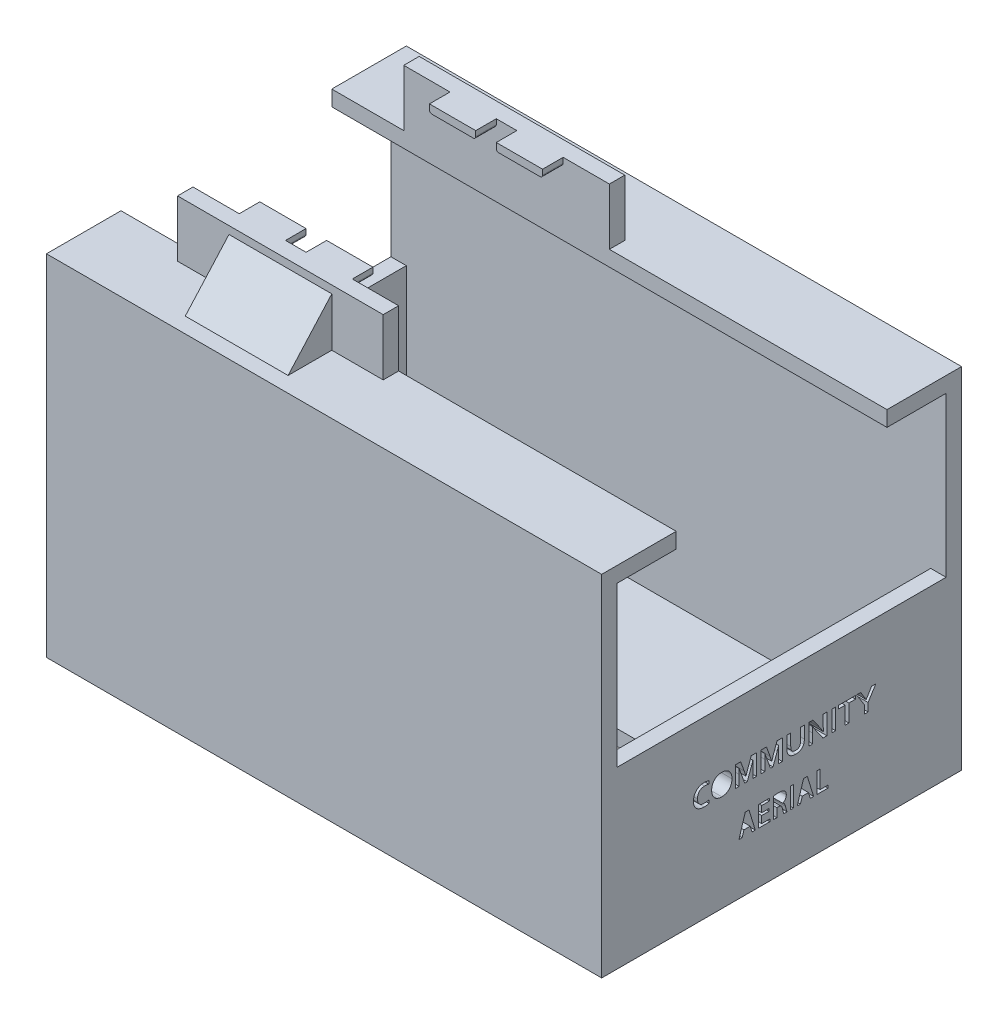
SolidWorks part; units mm, degrees
ref_plane "Alzado" through (0, 0, 0) normal (0, 0, 1) x (1, 0, 0)
ref_plane "Planta" through (0, 0, 0) normal (0, 1, 0) x (1, 0, 0)
ref_plane "Vista lateral" through (0, 0, 0) normal (1, 0, 0) x (0, 0, -1)
sketch "Croquis1" plane through (0, 0, 0) normal (0, 1, 0) x (1, 0, 0)
  line L0 (-2, 20.5) -> (-2, -20.5)
  line L1 (-20, -23.5) -> (20, -23.5)
  line L2 (-20, -23.5) -> (-20, 23.5)
  line L3 (-20, 23.5) -> (20, 23.5)
  line L4 (20, -23.5) -> (20, 23.5)
  line L5 (17, -20.5) -> (2, -20.5)
  line L6 (17, -20.5) -> (17, 20.5)
  line L7 (17, 20.5) -> (2, 20.5)
  line L8 (-17, -20.5) -> (-17, 20.5)
  line L9 (2, 20.5) -> (2, -20.5)
  line L10 (-2, -20.5) -> (-17, -20.5)
  line L11 (-2, 20.5) -> (-17, 20.5)
  line L12 (-55, 0) -> (55, 0) construction
  point P0 (0, 0)
  point P6 (0, 0)
  point P15 (-17, 0)
  dimension "D1" = 47
  dimension "D2" = 40
  dimension "D3" = 3
  dimension "D4" = 3
  dimension "D5" = 3
  dimension "D6" = 15
  dimension "D7" = 15
  dimension "D8" = 3
extrude "Saliente-Extruir1" add sketch "Croquis1" along normal blind 3
sketch "Croquis3" plane through (0, 3, 0) normal (0, 1, 0) x (1, 0, 0)
  line L0 (20, -23.5) -> (20, 23.5) construction
  line L1 (-20, 23.5) -> (20, 23.5)
  line L2 (-20, 23.5) -> (-20, 20.5)
  line L3 (-20, 20.5) -> (20, 20.5)
  line L4 (20, 23.5) -> (20, 20.5)
  line L6 (-20, -23.5) -> (20, -23.5)
  line L7 (-20, -23.5) -> (-20, -20.5)
  line L8 (-20, -20.5) -> (20, -20.5)
  line L9 (20, -23.5) -> (20, -20.5)
  dimension "D1" = 3
  dimension "D2" = 3
extrude "Saliente-Extruir2" add sketch "Croquis3" along normal blind 5
sketch "Croquis5" plane through (0, 0, -20.5) normal (0, 0, 1) x (1, 0, 0)
  line L0 (0, -55) -> (0, 55) construction
  line L1 (-10.5, 6.5) -> (-2.5, 6.5)
  line L2 (-11, 7) -> (-11, 8)
  line L3 (-11, 8) -> (-2, 8)
  line L4 (-2, 7) -> (-2, 8)
  line L5 (-11, 6.5) -> (-2, 8) construction
  line L6 (-11, 8) -> (-2, 6.5) construction
  line L7 (11, 8) -> (2, 6.5) construction
  line L8 (11, 6.5) -> (2, 8) construction
  line L9 (2, 7) -> (2, 8)
  line L10 (11, 8) -> (2, 8)
  line L11 (11, 7) -> (11, 8)
  line L12 (10.5, 6.5) -> (2.5, 6.5)
  line L13 (-20, 8) -> (20, 8) construction
  arc A0 (-2.5, 6.5) -> (-2, 7) centre (-2.5, 7) ccw
  arc A1 (-10.5, 6.5) -> (-11, 7) centre (-10.5, 7) cw
  arc A2 (10.5, 6.5) -> (11, 7) centre (10.5, 7) ccw
  arc A3 (2.5, 6.5) -> (2, 7) centre (2.5, 7) cw
  point P0 (-6.5, 7.25)
  point P11 (6.5, 7.25)
  dimension "D5" = 0.5
  dimension "D6" = 0.5
  dimension "D1" = 9
  dimension "D2" = 1.5
  dimension "D3" = 6.5
  dimension "D4" = 0
extrude "Saliente-Extruir3" add sketch "Croquis5" along normal blind 4
mirror "Simetría3" about plane through (0, 0, 0) normal (0, 0, 1) of "Saliente-Extruir3"
sketch "Croquis6" plane through (0, 0, 0) normal (0, -1, 0) x (1, 0, 0)
  line L0 (20, 23.5) -> (20, -23.5) construction
  line L1 (-20, 23.5) -> (20, 23.5)
  line L2 (-20, 23.5) -> (-20, 20.5)
  line L3 (-20, 20.5) -> (20, 20.5)
  line L4 (20, 23.5) -> (20, 20.5)
  line L5 (4.4, 0) -> (-4.4, 0) construction
  line L6 (20, -23.5) -> (20, -20.5)
  line L7 (-20, -20.5) -> (20, -20.5)
  line L8 (-20, -23.5) -> (-20, -20.5)
  line L9 (-20, -23.5) -> (20, -23.5)
  dimension "D1" = 3
extrude "Saliente-Extruir4" add sketch "Croquis6" along normal blind 3
ref_plane "Plano1" through (20, 0, 0) normal (1, 0, 0) x (0, 0, -1)
sketch "Croquis8" plane through (20, 0, 0) normal (1, 0, 0) x (0, 0, -1)
  line L1 (-32, -68) -> (32, -68)
  line L2 (-32, -68) -> (-32, -6)
  line L3 (-32, -6) -> (-20.5, -6)
  line L4 (32, -68) -> (32, -6)
  line L5 (20.5, -6) -> (32, -6)
  line L6 (20.5, -3) -> (35, -3)
  line L9 (-35, -71) -> (35, -71)
  line L10 (-35, -71) -> (-35, -3)
  line L11 (-35, -3) -> (-20.5, -3)
  line L12 (35, -71) -> (35, -3)
  line L16 (20.5, -3) -> (20.5, -6)
  line L17 (-20.5, -3) -> (-20.5, -6)
  point P0 (0, -37)
  point P11 (0, -37)
  dimension "D1" = 64
  dimension "D2" = 62
  dimension "D4" = 3
  dimension "D5" = 3
extrude "Saliente-Extruir5" add sketch "Croquis8" along normal mid plane 108
sketch "Croquis9" plane through (0, 0, 0) normal (0, 0, 1) x (1, 0, 0)
  line L0 (20, -38.5) -> (20, 38.5) construction
  line L1 (-34, -71) -> (-31, -71)
  line L2 (-34, -71) -> (-34, -37)
  line L3 (-34, -37) -> (-31, -37)
  line L4 (-31, -71) -> (-31, -37)
  line L5 (71, -71) -> (71, -37)
  line L6 (74, -37) -> (71, -37)
  line L7 (74, -71) -> (74, -37)
  line L8 (74, -71) -> (71, -71)
  dimension "D1" = 3
extrude "Saliente-Extruir6" add sketch "Croquis9" along normal mid plane 68
sketch "Croquis10" plane through (0, 0, 0) normal (1, 0, 0) x (0, 0, -1)
  line L1 (-20.5, -3) -> (20.5, -3)
  line L2 (-20.5, -3) -> (-20.5, 3)
  line L3 (-20.5, 3) -> (20.5, 3)
  line L4 (20.5, -3) -> (20.5, 3)
  line L5 (-20.5, -3) -> (20.5, 3) construction
  line L6 (-20.5, 3) -> (20.5, -3) construction
  point P0 (0, 0)
extrude "Cortar-Extruir1" cut sketch "Croquis10" against normal mid plane 68
sketch "Croquis11" plane through (0, 0, 0) normal (1, 0, 0) x (0, 0, -1)
  line L0 (-32, -3) -> (-23.5, 6.5)
  line L1 (-20.5, -3) -> (-35, -3) construction
  line L2 (-23.5, 8) -> (-23.5, -3) construction
rib "Nervio1" sketch "Croquis11" sketch "Croquis11" thickness 20 extrusion direction parallel to sketch draft on no parameters "D1"=20
mirror "Simetría4" about plane through (0, 0, 0) normal (0, 0, 1) of "Nervio1"
sketch "Croquis12" plane through (0, -71, 0) normal (0, -1, 0) x (1, 0, 0)
  line L0 (43.45, 0) -> (-43.45, 0) construction
  line L1 (11, -5.5) -> (71, -5.5)
  line L2 (11, -5.5) -> (11, 5.5)
  line L3 (11, 5.5) -> (71, 5.5)
  line L4 (71, -5.5) -> (71, 5.5)
  line L5 (11, -5.5) -> (71, 5.5) construction
  line L6 (11, 5.5) -> (71, -5.5) construction
  line L7 (74, 35) -> (74, -35) construction
  point P0 (41, 0)
  dimension "D1" = 11
  dimension "D2" = 33
  dimension "D3" = 60
extrude "Cortar-Extruir2" cut sketch "Croquis12" against normal blind 68
sketch "Croquis13" plane through (74, 0, 0) normal (1, 0, 0) x (0, 0, -1)
  line L0 (-21.5696, -52.1006) -> (21.5696, -52.1006) construction
  line L1 (0, 43.45) -> (0, -43.45) construction
  line L2 (-12.5252, -61.0353) -> (12.5252, -61.0353) construction
  text T0 "<b>COMMUNITY</b>" font "Corbel" height 4
  text T1 "<b>AERIAL</b>" font "Adobe Heiti Std R" height 4
  point P2 (0, -52.1006)
  point P8 (0, -61.0353)
extrude "Cortar-Extruir4" cut sketch "Croquis13" against normal blind 4
sketch "Croquis14" plane through (74, 0, 0) normal (1, 0, 0) x (0, 0, -1)
  line L0 (-7.4196, -59.3544) -> (-6.8994, -57.1681)
  line L1 (-6.8994, -57.1681) -> (-5.6422, -59.6435)
  line L2 (-5.6422, -59.6435) -> (-7.4196, -59.6435)
  line L3 (-7.4196, -59.6435) -> (-7.4196, -59.3544)
  line L4 (3.7944, -59.3544) -> (4.5491, -57.3556)
  line L5 (4.5491, -57.3556) -> (5.5829, -59.6435)
  line L6 (5.5829, -59.6435) -> (3.7944, -59.3544)
  circle A0 centre (-11.5944, -50.2575) radius 1.7339
  circle A1 centre (-0.4189, -58.1424) radius 0.9744
extrude "Cortar-Extruir5" cut sketch "Croquis14" against normal blind 4
